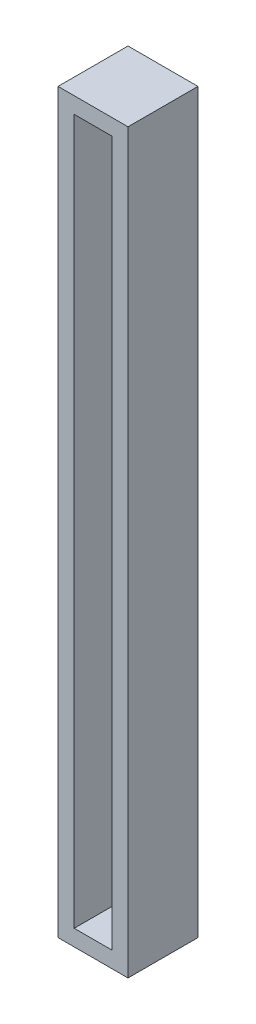
SolidWorks part; units mm, degrees
ref_plane "Front Plane" through (0, 0, 0) normal (0, 0, 1) x (1, 0, 0)
ref_plane "Top Plane" through (0, 0, 0) normal (0, 1, 0) x (1, 0, 0)
ref_plane "Right Plane" through (0, 0, 0) normal (1, 0, 0) x (0, 0, -1)
sketch "Sketch1" plane through (0, 0, 0) normal (0, 0, 1) x (1, 0, 0)
  line L0 (3.25, 0) -> (3.25, 68.5) construction
  line L1 (0, 0) -> (6.5, 0)
  line L2 (0, 0) -> (0, 68.5)
  line L3 (0, 68.5) -> (6.5, 68.5)
  line L4 (6.5, 0) -> (6.5, 68.5)
  line L5 (1.5, 1.5) -> (5, 1.5)
  line L6 (1.5, 1.5) -> (1.5, 67)
  line L7 (1.5, 67) -> (5, 67)
  line L8 (5, 1.5) -> (5, 67)
  line L9 (0, 34.25) -> (6.5, 34.25) construction
  dimension "D1" = 3.5
  dimension "D2" = 65.5
  dimension "D3" = 1.5
  dimension "D4" = 1.5
extrude "Boss-Extrude1" add sketch "Sketch1" along normal blind 6
sketch "Sketch2" plane through (0, 0, 0) normal (0, 0, -1) x (-1, 0, 0)
  line L1 (-6.5, 68.5) -> (0, 68.5)
  line L2 (-6.5, 68.5) -> (-6.5, 0)
  line L3 (-6.5, 0) -> (0, 0)
  line L4 (0, 68.5) -> (0, 0)
extrude "Boss-Extrude2" add sketch "Sketch2" along normal blind 0.5
sketch "Sketch3" plane through (0, 0, 0) normal (-1, 0, 0) x (0, 0, 1)
  line L0 (6, 68.5) -> (-0.5, 68.5) construction
  line L1 (1, 64) -> (1.5, 64)
  line L2 (0.5, 63.5) -> (0.5, 63)
  line L3 (1, 62.5) -> (1.5, 62.5)
  line L4 (2, 63.5) -> (2, 63)
  line L5 (6, 68.5) -> (6, 0) construction
  line L6 (-0.5, 34.25) -> (6, 34.25) construction
  line L7 (-0.5, 0) -> (-0.5, 68.5) construction
  line L8 (1, 6) -> (1.5, 6)
  line L9 (2, 5) -> (2, 5.5)
  line L10 (1, 4.5) -> (1.5, 4.5)
  line L11 (0.5, 5) -> (0.5, 5.5)
  arc A0 (2, 63) -> (1.5, 62.5) centre (1.5, 63) cw
  arc A1 (2, 63.5) -> (1.5, 64) centre (1.5, 63.5) ccw
  arc A2 (0.5, 63) -> (1, 62.5) centre (1, 63) ccw
  arc A3 (0.5, 63.5) -> (1, 64) centre (1, 63.5) cw
  arc A4 (2, 5.5) -> (1.5, 6) centre (1.5, 5.5) ccw
  arc A5 (2, 5) -> (1.5, 4.5) centre (1.5, 5) cw
  arc A6 (0.5, 5.5) -> (1, 6) centre (1, 5.5) cw
  arc A7 (0.5, 5) -> (1, 4.5) centre (1, 5) ccw
  point P10 (2, 62.5)
  point P13 (2, 64)
  point P16 (0.5, 62.5)
  dimension "D5" = 0.5
  dimension "D1" = 6
  dimension "D2" = 1.5
  dimension "D3" = 1.5
  dimension "D4" = 4
extrude "Boss-Extrude3" add sketch "Sketch3" along normal blind 1
